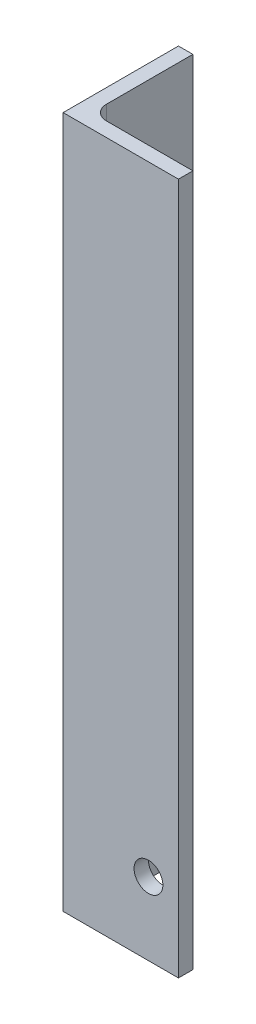
SolidWorks part; units mm, degrees
ref_plane "Front" through (0, 0, 0) normal (0, 0, 1) x (1, 0, 0)
ref_plane "Top" through (0, 0, 0) normal (0, 1, 0) x (1, 0, 0)
ref_plane "Right" through (0, 0, 0) normal (1, 0, 0) x (0, 0, -1)
sketch "Sketch1" plane through (0, 0, 0) normal (0, 1, 0) x (1, 0, 0)
  line L0 (0, 0) -> (0, -25.4)
  line L1 (0, -25.4) -> (25.4, -25.4)
  line L2 (25.4, -25.4) -> (25.4, -22.225)
  line L3 (25.4, -22.225) -> (3.175, -22.225)
  line L4 (3.175, -22.225) -> (3.175, 0)
  line L5 (3.175, 0) -> (0, 0)
  dimension "D1" = 3.175
  dimension "D2" = 3.175
  dimension "D3" = 25.4
  dimension "D4" = 25.4
extrude "Boss-Extrude1" add sketch "Sketch1" along normal blind 152.4
fillet "Fillet2" radius 3.175 1 edges at (3.175, 76.2, 22.225)
sketch "Sketch3" plane through (0, 0, 0) normal (-1, 0, 0) x (0, 0, 1)
  line L0 (-154.051, 25.4) -> (16.129, 25.4) construction
  line L1 (16.129, 25.4) -> (16.129, 6.35) construction
  line L2 (0, 152.4) -> (0, 0) construction
  circle A0 centre (6.604, 15.875) radius 3.175
  dimension "D1" = 6.35
  dimension "D2" = 9.525
  dimension "D3" = 9.525
extrude "Cut-Extrude2" cut sketch "Sketch3" against normal through all
sketch "Sketch4" plane through (0, 0, 25.4) normal (0, 0, 1) x (1, 0, 0)
  line L0 (0, 0) -> (25.4, 0) construction
  line L1 (25.4, 152.4) -> (25.4, 0) construction
  circle A0 centre (18.796, 16.002) radius 3.175
  dimension "D1" = 6.35
  dimension "D2" = 16.002
  dimension "D3" = 6.604
extrude "Cut-Extrude3" cut sketch "Sketch4" against normal up to next
